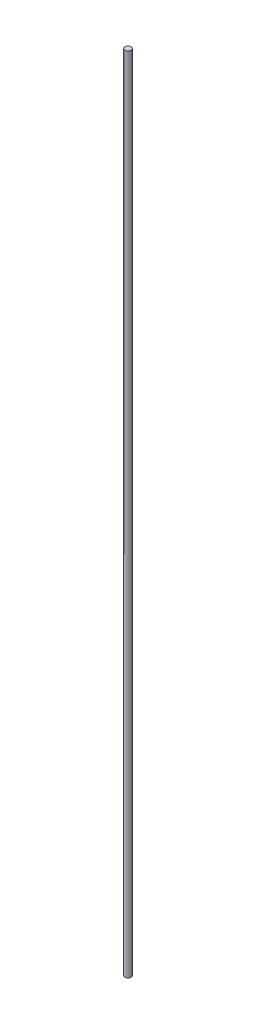
SolidWorks part; units mm, degrees
material "Custom Plastic"
ref_plane "Front Plane" through (0, 0, 0) normal (0, 0, 1) x (1, 0, 0)
ref_plane "Top Plane" through (0, 0, 0) normal (0, 1, 0) x (1, 0, 0)
ref_plane "Right Plane" through (0, 0, 0) normal (1, 0, 0) x (0, 0, -1)
sketch "Sketch1" plane through (0, 0, 0) normal (0, 1, 0) x (1, 0, 0)
  circle A0 centre (0, 0) radius 2
  dimension "D1" = 4
extrude "Boss-Extrude2" add sketch "Sketch1" along normal blind 520
cosmetic thread "Cosmetic Thread4" parameters "D2"=3.22
